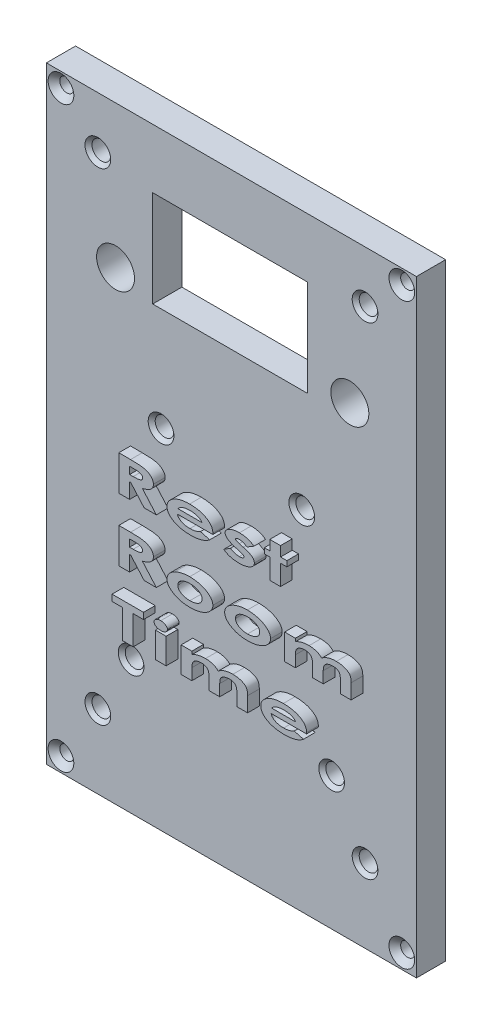
SolidWorks part; units mm, degrees
ref_plane "Piano frontale" through (0, 0, 0) normal (0, 0, 1) x (1, 0, 0)
ref_plane "Piano superiore" through (0, 0, 0) normal (0, 1, 0) x (1, 0, 0)
ref_plane "Piano destro" through (0, 0, 0) normal (1, 0, 0) x (0, 0, -1)
sketch "Schizzo1" plane through (0, 0, 0) normal (0, 0, 1) x (1, 0, 0)
  line L0 (77.34, 47.98) -> (77.34, -56)
  line L5 (58.6997, 37.8376) -> (32.1997, 37.8376)
  line L6 (58.6997, 37.8376) -> (58.6997, 21.3376)
  line L7 (58.6997, 21.3376) -> (32.1997, 21.3376)
  line L8 (32.1997, 37.8376) -> (32.1997, 21.3376)
  line L9 (77.34, -56) -> (14, -56)
  line L10 (14, 47.98) -> (14, -56)
  line L11 (77.34, 47.98) -> (14, 47.98)
  circle A0 centre (68.5477, 39.1333) radius 1.6
  circle A1 centre (22.8135, 39.1333) radius 1.6
  circle A2 centre (68.5477, -43.3771) radius 1.6
  circle A3 centre (22.8135, -43.3771) radius 1.6
  circle A4 centre (57.7111, 3.5977) radius 1.6
  circle A5 centre (33.6306, 3.5977) radius 1.6
  circle A6 centre (62.83, -33.235) radius 1.6
  circle A7 centre (28.5042, -33.235) radius 1.6
  circle A8 centre (65.9441, 23.5591) radius 3.25
  circle A9 centre (25.8413, 23.5591) radius 3.25
  dimension "D1" = 3.2
  dimension "D2" = 6.5
  dimension "D3" = 3.2
  dimension "D4" = 16.5
  dimension "D5" = 26.5
  dimension "D6" = 63.34
  dimension "D7" = 103.98
extrude "Estrusione-Estrusione1" add sketch "Schizzo1" along normal blind 5
hole_wizard "Foro svasato per Vite M2-1" positions "Schizzo6" profile "Schizzo7" countersink size "M2" standard "Ansi Metric" end condition through all
sketch "Schizzo6" plane through (0, 0, 5) normal (0, 0, 1) x (1, 0, 0)
  line L0 (14, 47.98) -> (14, -56) construction
  line L1 (77.34, 47.98) -> (14, 47.98) construction
  line L2 (77.34, -56) -> (77.34, 47.98) construction
  line L3 (14, -56) -> (77.34, -56) construction
  point P0 (16.5, 45.48)
  point P2 (74.84, 45.48)
  point P4 (74.84, -53.5)
  point P6 (16.5, -53.5)
  dimension "D1" = 2.5
  dimension "D2" = 2.5
  dimension "D3" = 2.5
  dimension "D4" = 2.5
  dimension "D5" = 2.5
  dimension "D6" = 2.5
  dimension "D7" = 2.5
  dimension "D8" = 2.5
sketch "Schizzo7" plane through (16.5, 45.48, 5) normal (1, 0, 0) x (0, -1, 0)
  line L0 (0, 0) -> (0, 5)
  line L1 (0, 5) -> (1.2, 5)
  line L2 (1.2, 5) -> (1.2, 1)
  line L3 (1.2, 1) -> (2.2, 0)
  line L5 (2.2, 0) -> (0, 0)
  line L6 (-1.2, 1) -> (-2.2, 0) construction
  line L11 (0, -6.35) -> (0, 107.95) construction
  dimension "Thru Hole Dia." = 2.4
  dimension "Thru Hole Depth" = 5
  dimension "Near C'Sink Dia." = 4.4
  dimension "Near C'Sink Angle" = 90
hole_wizard "Foro svasato per Vite M2-2" positions "Schizzo8" profile "Schizzo9" countersink size "M2" standard "Ansi Metric" end condition through all
sketch "Schizzo8" plane through (0, 0, 5) normal (0, 0, 1) x (1, 0, 0)
  point P0 (33.6306, 3.5977)
  point P3 (57.7111, 3.5977)
  point P6 (62.83, -33.235)
  point P9 (28.5042, -33.235)
  point P12 (22.8135, -43.3771)
  point P15 (68.5477, -43.3771)
  point P18 (68.5477, 39.1333)
  point P21 (22.8135, 39.1333)
sketch "Schizzo9" plane through (33.6306, 3.5977, 5) normal (1, 0, 0) x (0, -1, 0)
  line L0 (0, 0) -> (0, 5)
  line L1 (0, 5) -> (1.2, 5)
  line L2 (1.2, 5) -> (1.2, 1)
  line L3 (1.2, 1) -> (2.2, 0)
  line L5 (2.2, 0) -> (0, 0)
  line L6 (-1.2, 1) -> (-2.2, 0) construction
  line L11 (0, -6.35) -> (0, 107.95) construction
  dimension "Thru Hole Dia." = 2.4
  dimension "Thru Hole Depth" = 5
  dimension "Near C'Sink Dia." = 4.4
  dimension "Near C'Sink Angle" = 90
sketch "Schizzo10" plane through (0, 0, 5) normal (0, 0, 1) x (1, 0, 0)
  text T0 "Rest\r\nRoom\r\nTime" font "Century Gothic" height 6
extrude "Estrusione-Estrusione3" add sketch "Schizzo10" along normal blind 2
